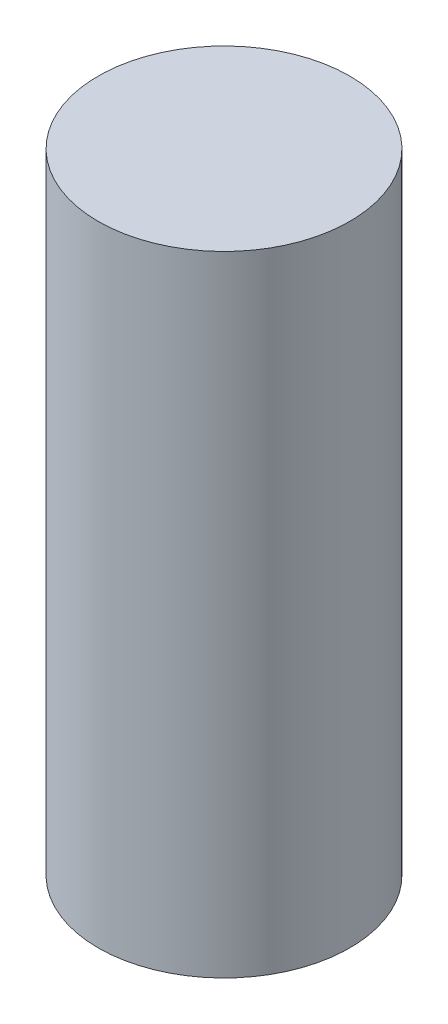
SolidWorks part; units mm, degrees
ref_plane "Front Plane" through (0, 0, 0) normal (0, 0, 1) x (1, 0, 0)
ref_plane "Top Plane" through (0, 0, 0) normal (0, 1, 0) x (1, 0, 0)
ref_plane "Right Plane" through (0, 0, 0) normal (1, 0, 0) x (0, 0, -1)
sketch "Sketch1" plane through (0, 0, 0) normal (0, 1, 0) x (1, 0, 0)
  circle A0 centre (0, 0) radius 20
  dimension "D1" = 40
extrude "Boss-Extrude1" add sketch "Sketch1" along normal blind 100
